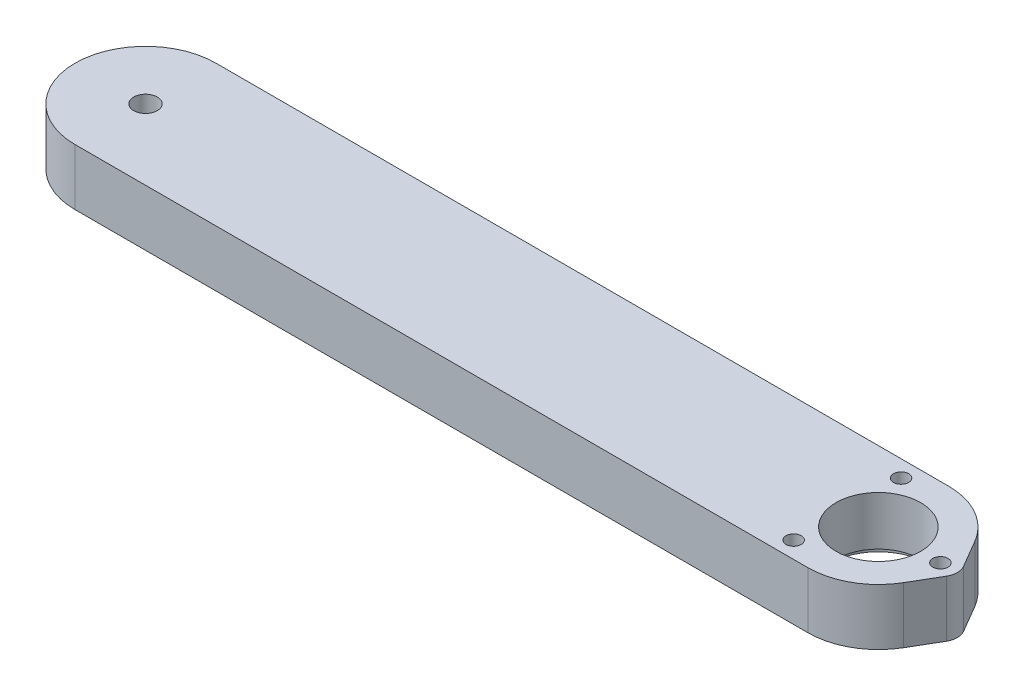
SolidWorks part; units mm, degrees
ref_plane "前视基准面" through (0, 0, 0) normal (0, 0, 1) x (1, 0, 0)
ref_plane "上视基准面" through (0, 0, 0) normal (0, 1, 0) x (1, 0, 0)
ref_plane "右视基准面" through (0, 0, 0) normal (1, 0, 0) x (0, 0, -1)
sketch "草图1" plane through (0, 0, 0) normal (0, 1, 0) x (1, 0, 0)
  line L0 (-65, 0) -> (65, 0) construction
  line L1 (-65, 12.5) -> (65, 12.5)
  line L2 (-65, -12.5) -> (65, -12.5)
  arc A0 (-65, 12.5) -> (-65, -12.5) centre (-65, 0) ccw
  arc A1 (65, -12.5) -> (65, 12.5) centre (65, 0) ccw
  point P2 (0, 0)
  dimension "D2" = 12.5
  dimension "D1" = 130
extrude "凸台-拉伸1" add sketch "草图1" along normal blind 10
sketch "草图10" plane through (0, 0, 0) normal (0, -1, 0) x (1, 0, 0)
  line L0 (75.7955, -6.3014) -> (78.5909, -1.5123)
  line L3 (75.7955, 6.3014) -> (78.5909, 1.5123)
  line L4 (75.7955, -6.3014) -> (75.7955, 6.3014)
  line L5 (76, 0) -> (77.5, 0) construction
  circle A5 centre (76, 0) radius 3 construction
  arc A6 (65, -12.5) -> (65, 12.5) centre (65, 0) ccw construction
  arc A7 (78.5909, -1.5123) -> (78.5909, 1.5123) centre (76, 0) ccw
  dimension "D1" = 6
  dimension "D2" = 1.5
extrude "凸台-拉伸5" add sketch "草图10" against normal up to surface (10 mm away) up to face at (0, 10, 0)
sketch "草图7" plane through (0, 10, 0) normal (0, 1, 0) x (1, 0, 0)
  circle A0 centre (65, 0) radius 7.5
  dimension "D1" = 15
extrude "切除-拉伸2" cut sketch "草图7" against normal up to next
sketch "草图8" plane through (0, 0, 0) normal (0, 1, 0) x (1, 0, 0)
  circle A0 centre (65, 0) radius 8.75
  dimension "D1" = 17.5
extrude "切除-拉伸3" cut sketch "草图8" along normal blind 1.3
sketch "草图9" plane through (0, 0, 0) normal (0, -1, 0) x (1, 0, 0)
  line L0 (65, 0) -> (54, 0) construction
  line L1 (65, 0) -> (59.5, 9.5263) construction
  circle A0 centre (65, 0) radius 11 construction
  circle A5 centre (59.5, 9.5263) radius 1.35
  circle A9 centre (76, 0) radius 1.35
  circle A10 centre (59.5, -9.5263) radius 1.35
  point P12 (65, 0)
  point P15 (65, 0)
  dimension "22" = 22
  dimension "D3" = 2.7
  dimension "D2" = 60
  dimension "D1" = 3
extrude "切除-拉伸4" cut sketch "草图9" against normal up to next
sketch "草图12" plane through (0, 10, 0) normal (0, 1, 0) x (1, 0, 0)
  circle A0 centre (-65, 0) radius 2.1
  dimension "D1" = 4.2
extrude "切除-拉伸5" cut sketch "草图12" against normal up to next
sketch "草图13" plane through (0, 10, 0) normal (0, 1, 0) x (1, 0, 0)
  line L0 (-45, 0) -> (45, 0) construction
  line L1 (-45, 8) -> (45, 8)
  line L2 (-45, -8) -> (45, -8)
  arc A0 (-45, 8) -> (-45, -8) centre (-45, 0) ccw
  arc A1 (45, -8) -> (45, 8) centre (45, 0) ccw
  point P2 (0, 0)
  dimension "D1" = 8
  dimension "D2" = 90
extrude "切除-拉伸6" [suppressed] cut sketch "草图13" against normal up to next
sketch "草图14" [suppressed] plane through (0, 5, 0) normal (0, 1, 0) x (1, 0, 0)
  line L5 (-45, -8) -> (45, -8) construction
  line L6 (45, 8) -> (-45, 8) construction
  line L7 (0, -8) -> (9.2376, 8)
  line L8 (9.2376, 8) -> (13.2376, 8)
  line L9 (13.2376, 8) -> (4, -8)
  line L10 (4, -8) -> (0, -8)
  dimension "D1" = 4
  dimension "D2" = 60
extrude "凸台-拉伸6" [suppressed] add sketch "草图14" against normal up to surface (5 mm away)
pattern_linear "阵列(线性)1" [suppressed] count 3 spacing 25 count 2 spacing 25
mirror "镜向1" [suppressed] about plane through (0, 0, 0) normal (1, 0, 0)
